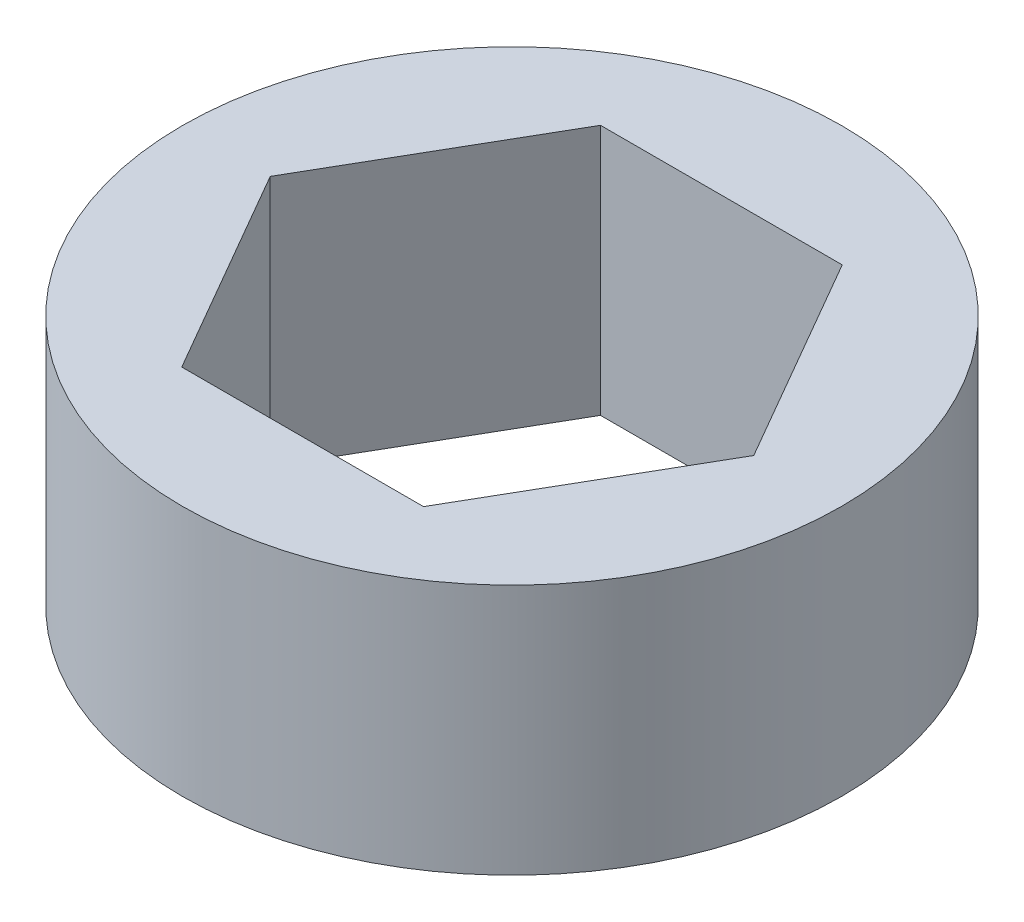
SolidWorks part; units mm, degrees
ref_plane "Front Plane" through (0, 0, 0) normal (0, 0, 1) x (1, 0, 0)
ref_plane "Top Plane" through (0, 0, 0) normal (0, 1, 0) x (1, 0, 0)
ref_plane "Right Plane" through (0, 0, 0) normal (1, 0, 0) x (0, 0, -1)
sketch "Sketch1" plane through (0, 0, 0) normal (0, 1, 0) x (1, 0, 0)
  line L1 (-7.3323, 0) -> (-3.6662, -6.35)
  line L2 (-3.6662, -6.35) -> (3.6662, -6.35)
  line L3 (3.6662, -6.35) -> (7.3323, 0)
  line L4 (7.3323, 0) -> (3.6662, 6.35)
  line L5 (3.6662, 6.35) -> (-3.6662, 6.35)
  line L6 (-3.6662, 6.35) -> (-7.3323, 0)
  circle A0 centre (0, 0) radius 10
  circle A1 centre (0, 0) radius 6.35 construction
  dimension "D2" = 20
  dimension "D1" = 12.7
extrude "Boss-Extrude1" add sketch "Sketch1" along normal blind 7.62
